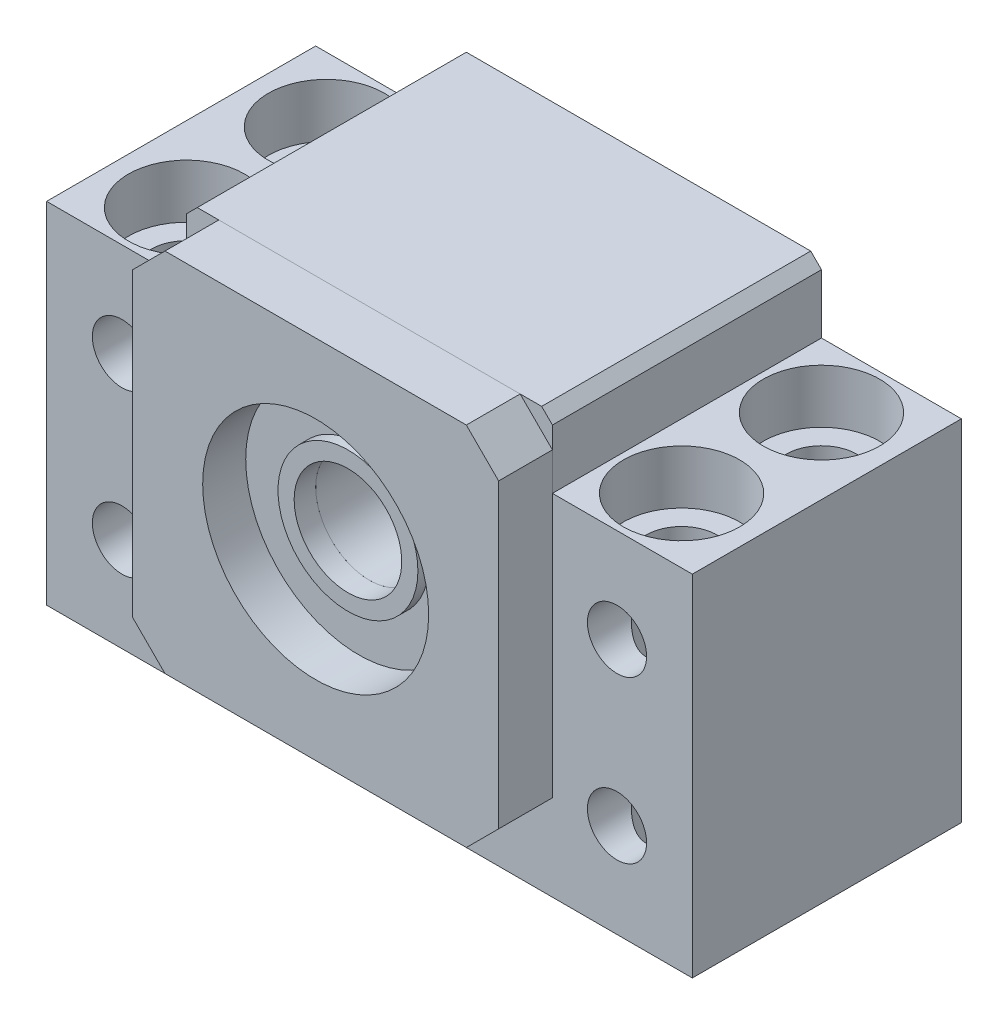
SolidWorks part; units mm, degrees
material "1.0037 (S235JR)"
ref_plane "Ebene vorne" through (0, 0, 0) normal (0, 0, 1) x (1, 0, 0)
ref_plane "Ebene oben" through (0, 0, 0) normal (0, 1, 0) x (1, 0, 0)
ref_plane "Ebene rechts" through (0, 0, 0) normal (1, 0, 0) x (0, 0, -1)
sketch "Skizze1" plane through (0, 0, 0) normal (0, 0, 1) x (1, 0, 0)
  line L0 (0, 0) -> (0, 46.2844) construction
  line L1 (-30, 0) -> (30, 0)
  line L2 (30, 0) -> (30, 32.5)
  line L3 (30, 32.5) -> (17, 32.5)
  line L4 (17, 32.5) -> (17, 38)
  line L5 (16, 39) -> (-16, 39)
  line L6 (17, 38) -> (16, 39)
  line L7 (-17, 38) -> (-16, 39)
  line L8 (-17, 32.5) -> (-17, 38)
  line L9 (-30, 32.5) -> (-17, 32.5)
  line L10 (-30, 0) -> (-30, 32.5)
  point P7 (17, 39)
  point P12 (0, 39)
  dimension "D1" = 60
  dimension "D2" = 34
  dimension "D4" = 32.5
  dimension "D5" = 39
extrude "Aufsatz-Linear austragen1" add sketch "Skizze1" along normal blind 25
sketch "Skizze2" plane through (0, 0, 25) normal (0, 0, 1) x (1, 0, 0)
  line L0 (0, 0) -> (0, 41.7908) construction
  line L1 (-14, 39) -> (14, 39)
  line L2 (17, 36) -> (17, 8)
  line L3 (14, 5) -> (-14, 5)
  line L4 (16, 39) -> (-16, 39) construction
  line L5 (14, 39) -> (17, 36)
  line L6 (17, 8) -> (14, 5)
  line L7 (-17, 8) -> (-14, 5)
  line L8 (-17, 36) -> (-17, 8)
  line L9 (-14, 39) -> (-17, 36)
  line L10 (17, 32.5) -> (17, 38) construction
  point P4 (17, 39)
  point P6 (17, 5)
  point P14 (0, 5)
  point P17 (0, 39)
  dimension "D1" = 34
extrude "Aufsatz-Linear austragen2" add sketch "Skizze2" along normal blind 5 separate body
sketch "Skizze3" plane through (0, 0, 30) normal (0, 0, 1) x (1, 0, 0)
  line L0 (0, 0) -> (0, 42.014) construction
  line L1 (-12.8891, 22) -> (13.2796, 22) construction
  line L2 (-30, 0) -> (30, 0) construction
  circle A0 centre (0, 22) radius 5
  dimension "D2" = 10
  dimension "D1" = 22
extrude "Schnitt-Linear austragen1" cut sketch "Skizze3" against normal blind 50
sketch "Skizze4" plane through (0, 32.5, 0) normal (0, 1, 0) x (1, 0, 0)
  line L0 (0, 0) -> (0, -31.5995) construction
  line L1 (23, -6) -> (23, -19) construction
  line L2 (30, 0) -> (17, 0) construction
  circle A0 centre (23, -6) radius 3.3
  circle A1 centre (23, -19) radius 3.3
  circle A2 centre (-23, -6) radius 3.3
  circle A3 centre (-23, -19) radius 3.3
  dimension "D1" = 46
  dimension "D2" = 6
  dimension "D3" = 13
  dimension "D4" = 6.6
extrude "Schnitt-Linear austragen2" cut sketch "Skizze4" against normal blind 50
sketch "Skizze5" plane through (0, 32.5, 0) normal (0, 1, 0) x (1, 0, 0)
  line L0 (0, 0) -> (0, -34.9473) construction
  circle A0 centre (23, -6) radius 5.4
  circle A1 centre (23, -19) radius 5.4
  circle A2 centre (-23, -19) radius 5.4
  circle A3 centre (-23, -6) radius 5.4
  dimension "D1" = 10.8
extrude "Schnitt-Linear austragen3" cut sketch "Skizze5" against normal blind 5
sketch "Skizze6" plane through (0, 0, 25) normal (0, 0, 1) x (1, 0, 0)
  line L0 (0, 0) -> (0, 41.5676) construction
  line L1 (23, 23.75) -> (23, 8.75) construction
  line L3 (30, 16.25) -> (23, 16.25) construction
  line L4 (30, 0) -> (30, 32.5) construction
  circle A0 centre (23, 23.75) radius 2.75
  circle A1 centre (23, 8.75) radius 2.75
  circle A2 centre (-23, 23.75) radius 2.75
  circle A3 centre (-23, 8.75) radius 2.75
  dimension "D1" = 5.5
  dimension "D2" = 15
  dimension "D3" = 46
extrude "Schnitt-Linear austragen4" cut sketch "Skizze6" against normal blind 50
sketch "Skizze7" plane through (0, 0, 30) normal (0, 0, -1) x (-1, 0, 0)
  circle A0 centre (0, 22) radius 10.5
  point P3 (0, 0)
  dimension "D1" = 21
extrude "Schnitt-Linear austragen6" cut sketch "Skizze7" along normal blind 3
sketch "Skizze8" plane through (0, 0, 0) normal (0, 0, -1) x (-1, 0, 0)
  circle A0 centre (0, 22) radius 6.5
  circle A1 centre (0, 22) radius 10.5
  dimension "D1" = 13
  dimension "D2" = 21
extrude "Schnitt-Linear austragen7" cut sketch "Skizze8" against normal blind 1.5
sketch "Skizze9" plane through (0, 0, 27) normal (0, 0, 1) x (1, 0, 0)
  circle A0 centre (0, 22) radius 6.5
  circle A1 centre (0, 22) radius 10.5 construction
  circle A2 centre (0, 22) radius 10.5
  dimension "D1" = 13
extrude "Schnitt-Linear austragen8" cut sketch "Skizze9" against normal blind 1
